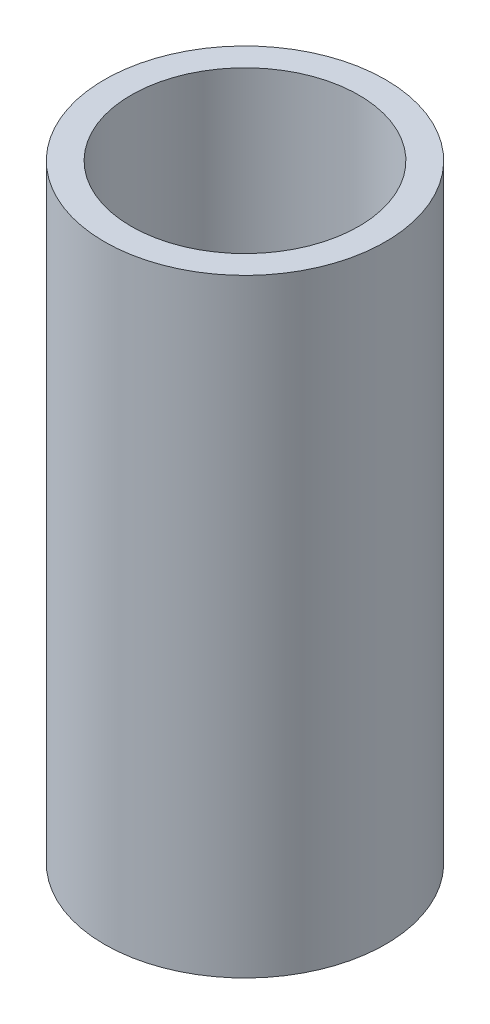
SolidWorks part; units mm, degrees
material "AISI 4130 Steel, annealed at 865C"
ref_plane "Front Plane" through (0, 0, 0) normal (0, 0, 1) x (1, 0, 0)
ref_plane "Top Plane" through (0, 0, 0) normal (0, 1, 0) x (1, 0, 0)
ref_plane "Right Plane" through (0, 0, 0) normal (1, 0, 0) x (0, 0, -1)
sketch "Sketch2" plane through (0, 0, 0) normal (0, 1, 0) x (1, 0, 0)
  circle A0 centre (0, 0) radius 10.287
  circle A1 centre (0, 0) radius 12.7
  dimension "D1" = 25.4
  dimension "D2" = 2.413
extrude "Boss-Extrude1" add sketch "Sketch2" along normal blind 55
